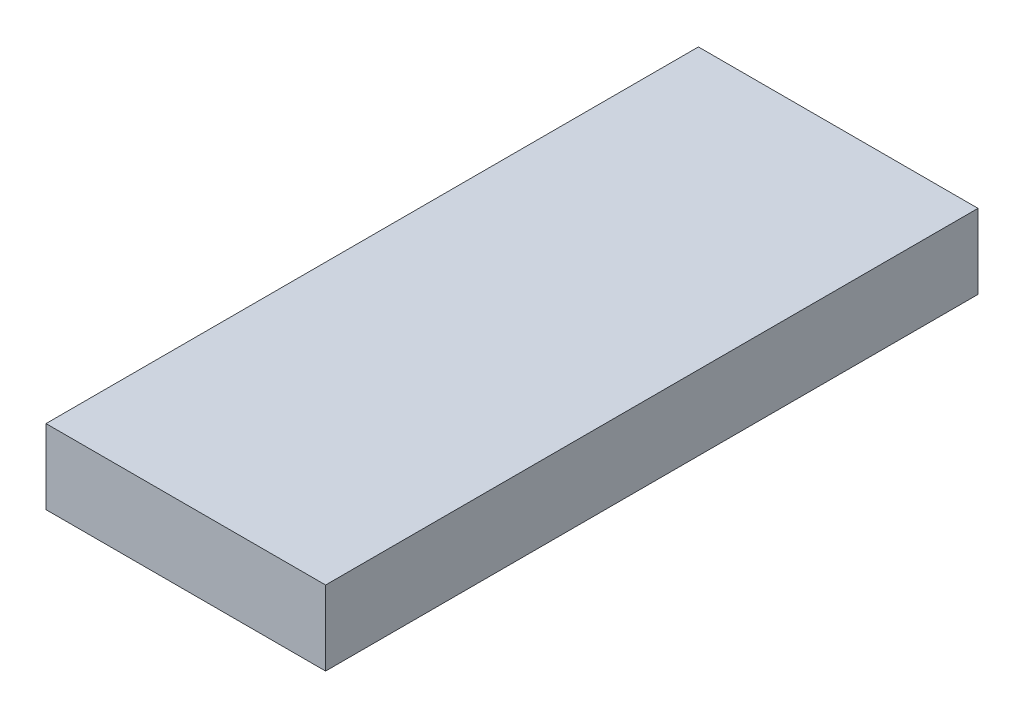
SolidWorks part; units mm, degrees
material "Nickel"
ref_plane "Front Plane" through (0, 0, 0) normal (0, 0, 1) x (1, 0, 0)
ref_plane "Top Plane" through (0, 0, 0) normal (0, 1, 0) x (1, 0, 0)
ref_plane "Right Plane" through (0, 0, 0) normal (1, 0, 0) x (0, 0, -1)
sketch "Sketch1" plane through (0, 0, 0) normal (0, 1, 0) x (1, 0, 0)
  line L1 (0, 0) -> (7.5, 0)
  line L2 (0, 0) -> (0, 17.5)
  line L3 (0, 17.5) -> (7.5, 17.5)
  line L4 (7.5, 0) -> (7.5, 17.5)
  dimension "D1" = 17.5
  dimension "D2" = 7.5
extrude "Boss-Extrude1" add sketch "Sketch1" along normal blind 2
